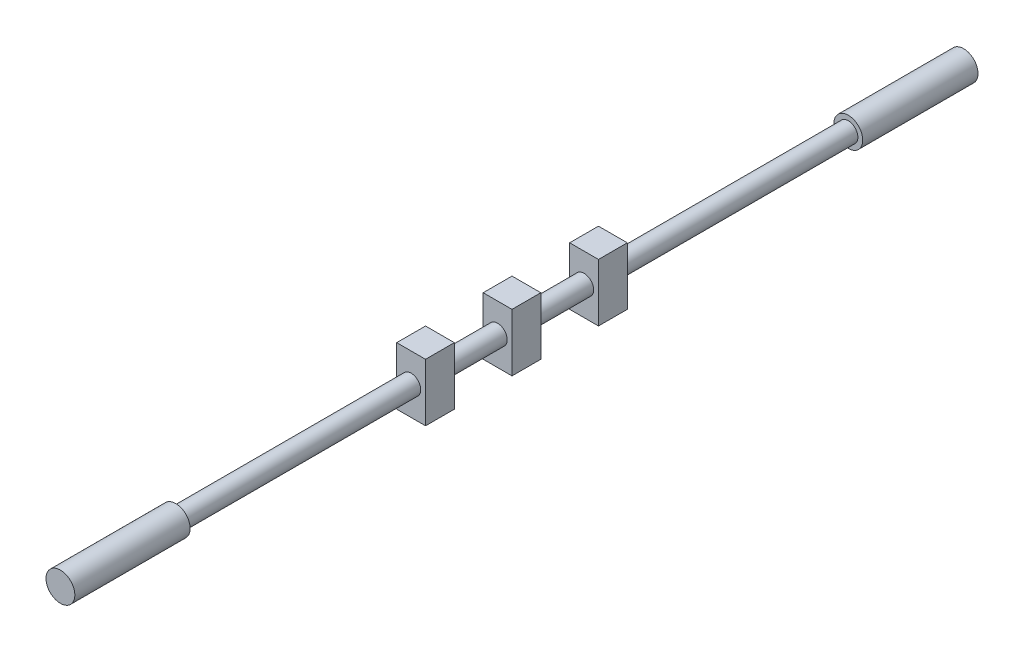
SolidWorks part; units mm, degrees
ref_plane "Front Plane" through (0, 0, 0) normal (0, 0, 1) x (1, 0, 0)
ref_plane "Top Plane" through (0, 0, 0) normal (0, 1, 0) x (1, 0, 0)
ref_plane "Right Plane" through (0, 0, 0) normal (1, 0, 0) x (0, 0, -1)
sketch "Sketch1" plane through (0, 0, 0) normal (0, 0, 1) x (1, 0, 0)
  circle A0 centre (0, 0) radius 25.4
  dimension "D1" = 50.8
extrude "Boss-Extrude1" add sketch "Sketch1" along normal blind 1778
sketch "Sketch2" plane through (0, 0, 1778) normal (0, 0, 1) x (1, 0, 0)
  circle A0 centre (0, 0) radius 38.1
extrude "Boss-Extrude2" add sketch "Sketch2" along normal blind 304.8
sketch "Sketch3" plane through (0, 0, 0) normal (0, 0, -1) x (-1, 0, 0)
  circle A0 centre (0, 0) radius 38.1
extrude "Boss-Extrude3" add sketch "Sketch3" along normal blind 304.8
sketch "Sketch4" plane through (0, 0, 0) normal (0, 1, 0) x (1, 0, 0)
  line L0 (-25.4, 0) -> (-25.4, -1778) construction
  line L1 (-38.1, -850.9) -> (38.1, -850.9)
  line L2 (-38.1, -850.9) -> (-38.1, -927.1)
  line L3 (-38.1, -927.1) -> (38.1, -927.1)
  line L4 (38.1, -850.9) -> (38.1, -927.1)
  line L5 (38.1, -1778) -> (-38.1, -1778) construction
  line L6 (-38.1, -1079.5) -> (38.1, -1079.5)
  line L7 (-38.1, -1079.5) -> (-38.1, -1155.7)
  line L8 (-38.1, -1155.7) -> (38.1, -1155.7)
  line L9 (38.1, -1079.5) -> (38.1, -1155.7)
  line L10 (-38.1, -622.3) -> (38.1, -622.3)
  line L11 (-38.1, -622.3) -> (-38.1, -698.5)
  line L12 (-38.1, -698.5) -> (38.1, -698.5)
  line L13 (38.1, -622.3) -> (38.1, -698.5)
  point P16 (38.1, -889)
  dimension "D1" = 76.2
  dimension "D2" = 12.7
  dimension "D3" = 76.2
  dimension "D4" = 76.2
  dimension "D5" = 12.7
  dimension "D6" = 76.2
  dimension "D7" = 76.2
  dimension "D8" = 12.7
  dimension "D9" = 76.2
  dimension "D10" = 889
  dimension "D11" = 152.4
  dimension "D12" = 152.4
extrude "Boss-Extrude4" add sketch "Sketch4" along normal mid plane 152.4
